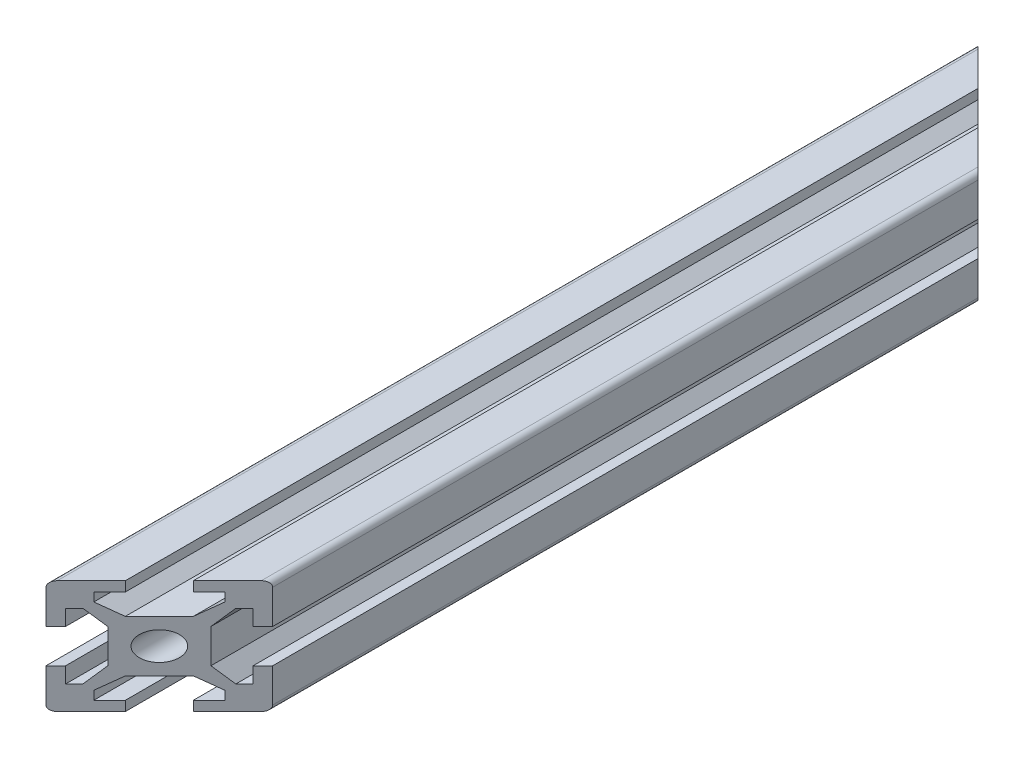
SolidWorks part; units mm, degrees
ref_plane "Front Plane" through (0, 0, 0) normal (0, 0, 1) x (1, 0, 0)
ref_plane "Top Plane" through (0, 0, 0) normal (0, 1, 0) x (1, 0, 0)
ref_plane "Right Plane" through (0, 0, 0) normal (1, 0, 0) x (0, 0, -1)
sketch "Sketch1" plane through (0, 0, 0) normal (0, 0, 1) x (1, 0, 0)
  line L18 (0, 0) -> (0, 20.5117) construction
  line L39 (-10, 10) -> (-3, 10)
  line L41 (10, 10) -> (3, 10)
  line L43 (-10, 10) -> (-10, 3)
  line L45 (-10, -10) -> (-10, -3)
  line L47 (-10, -10) -> (-3, -10)
  line L49 (3, -10) -> (10, -10)
  line L51 (10, -10) -> (10, -3)
  line L53 (10, 3) -> (10, 10)
  line L55 (-3, 10) -> (-3, 8.2726)
  line L56 (-3, 8.2726) -> (-5.7838, 8.2726)
  line L57 (-5.7838, 8.2726) -> (-5.7838, 6.748)
  line L58 (-5.7838, 6.748) -> (-3, 4.5508)
  line L59 (-3, 4.5508) -> (3, 4.5508)
  line L60 (3, 10) -> (3, 8.2726)
  line L61 (3, 8.2726) -> (5.7838, 8.2726)
  line L62 (5.7838, 8.2726) -> (5.7838, 6.748)
  line L63 (5.7838, 6.748) -> (3, 4.5508)
  line L64 (10, 3) -> (8.2726, 3)
  line L65 (8.2726, 3) -> (8.2726, 5.7838)
  line L66 (8.2726, 5.7838) -> (6.748, 5.7838)
  line L67 (10, -3) -> (8.2726, -3)
  line L68 (8.2726, -3) -> (8.2726, -5.7838)
  line L69 (8.2726, -5.7838) -> (6.748, -5.7838)
  line L70 (4.55, -2.9994) -> (4.55, 3.0006)
  line L71 (4.55, -2.9994) -> (6.748, -5.7838)
  line L72 (4.55, 3.0006) -> (6.748, 5.7838)
  line L73 (3, -10) -> (3, -8.2726)
  line L74 (3, -8.2726) -> (5.7838, -8.2726)
  line L75 (5.7838, -8.2726) -> (5.7838, -6.748)
  line L76 (-3, -10) -> (-3, -8.2726)
  line L77 (-3, -8.2726) -> (-5.7838, -8.2726)
  line L78 (-5.7838, -8.2726) -> (-5.7838, -6.748)
  line L79 (2.9994, -4.55) -> (-3.0006, -4.55)
  line L80 (5.7838, -6.748) -> (2.9994, -4.55)
  line L81 (-5.7838, -6.748) -> (-3.0006, -4.55)
  line L82 (-10, -3) -> (-8.2726, -3)
  line L83 (-8.2726, -3) -> (-8.2726, -5.7838)
  line L84 (-8.2726, -5.7838) -> (-6.748, -5.7838)
  line L85 (-10, 3) -> (-8.2726, 3)
  line L86 (-8.2726, 3) -> (-8.2726, 5.7838)
  line L87 (-8.2726, 5.7838) -> (-6.748, 5.7838)
  line L88 (-4.55, -3.0006) -> (-4.55, 2.9994)
  line L89 (-6.748, -5.7838) -> (-4.55, -3.0006)
  line L90 (-4.55, 2.9994) -> (-6.748, 5.7838)
  dimension "D9" = 7
  dimension "D17" = 2.7838
  dimension "D1" = 20
  dimension "D2" = 20
  dimension "D3" = 10
  dimension "D4" = 10
  dimension "D5" = 7
  dimension "D6" = 7
  dimension "D7" = 7
  dimension "D8" = 7
  dimension "D10" = 7
  dimension "D11" = 7
  dimension "D12" = 7
  dimension "D13" = 6
  dimension "D14" = 3
  dimension "D15" = 3.5464
  dimension "D16" = 1.5246
  dimension "D18" = 1.7274
  dimension "D19" = 4.55
  dimension "D20" = 4.55
  dimension "D21" = 4.55
  dimension "D22" = 10
  dimension "D23" = 10
  dimension "D24" = 10
  dimension "D25" = 10
  dimension "D26" = 10
  dimension "D27" = 10
  dimension "D28" = 6
  dimension "D29" = 6
  dimension "D30" = 6
  dimension "D31" = 6
extrude "Boss-Extrude1" add sketch "Sketch1" along normal mid plane 164.46
sketch "Sketch2" plane through (0, 0, 82.23) normal (0, 0, 1) x (1, 0, 0)
  circle A0 centre (0, 0) radius 2.5
  dimension "D1" = 5
extrude "Cut-Extrude1" cut sketch "Sketch2" against normal through all both and the other way through all
fillet "Fillet1" radius 1 4 edges at (-10, -10, 0) (10, -10, 0) (10, 10, 0) (-10, 10, 0)
ref_plane "Plane1" through (36.115, 0, -36.115) normal (-0.7071, 0, 0.7071) x (0.7071, 0, 0.7071)
sketch "Sketch3" plane through (36.115, 0, -36.115) normal (-0.7071, 0, 0.7071) x (0.7071, 0, 0.7071)
  line L0 (-65.2165, -3) -> (-65.2165, -9) construction
  line L1 (-70.3799, 11.0676) -> (-28.101, 11.0676)
  line L2 (-70.3799, 11.0676) -> (-70.3799, -10.9324)
  line L3 (-70.3799, -10.9324) -> (-28.101, -10.9324)
  line L4 (-28.101, 11.0676) -> (-28.101, -10.9324)
  line L5 (-64.5094, 10) -> (51.7814, 10) construction
  dimension "D1" = 22
  dimension "D2" = 42.2789
  dimension "D3" = 5.1634
  dimension "D4" = 1.0676
extrude "Cut-Extrude2" cut sketch "Sketch3" against normal through all
ref_plane "Plane2" through (36.115, 0, 36.115) normal (-0.7071, 0, -0.7071) x (-0.7071, 0, 0.7071)
sketch "Sketch4" plane through (36.115, 0, 36.115) normal (-0.7071, 0, -0.7071) x (-0.7071, 0, 0.7071)
  line L0 (65.2165, -3) -> (65.2165, -9) construction
  line L1 (70.1056, 11.0692) -> (35.1056, 11.0692)
  line L2 (70.1056, 11.0692) -> (70.1056, -11.0352)
  line L3 (70.1056, -11.0352) -> (35.1056, -11.0352)
  line L4 (35.1056, 11.0692) -> (35.1056, -11.0352)
  line L5 (64.5094, -10) -> (-51.0743, -10) construction
  dimension "D1" = 22.1045
  dimension "D2" = 35
  dimension "D3" = 4.8891
  dimension "D4" = 1.0352
extrude "Cut-Extrude3" cut sketch "Sketch4" against normal through all
